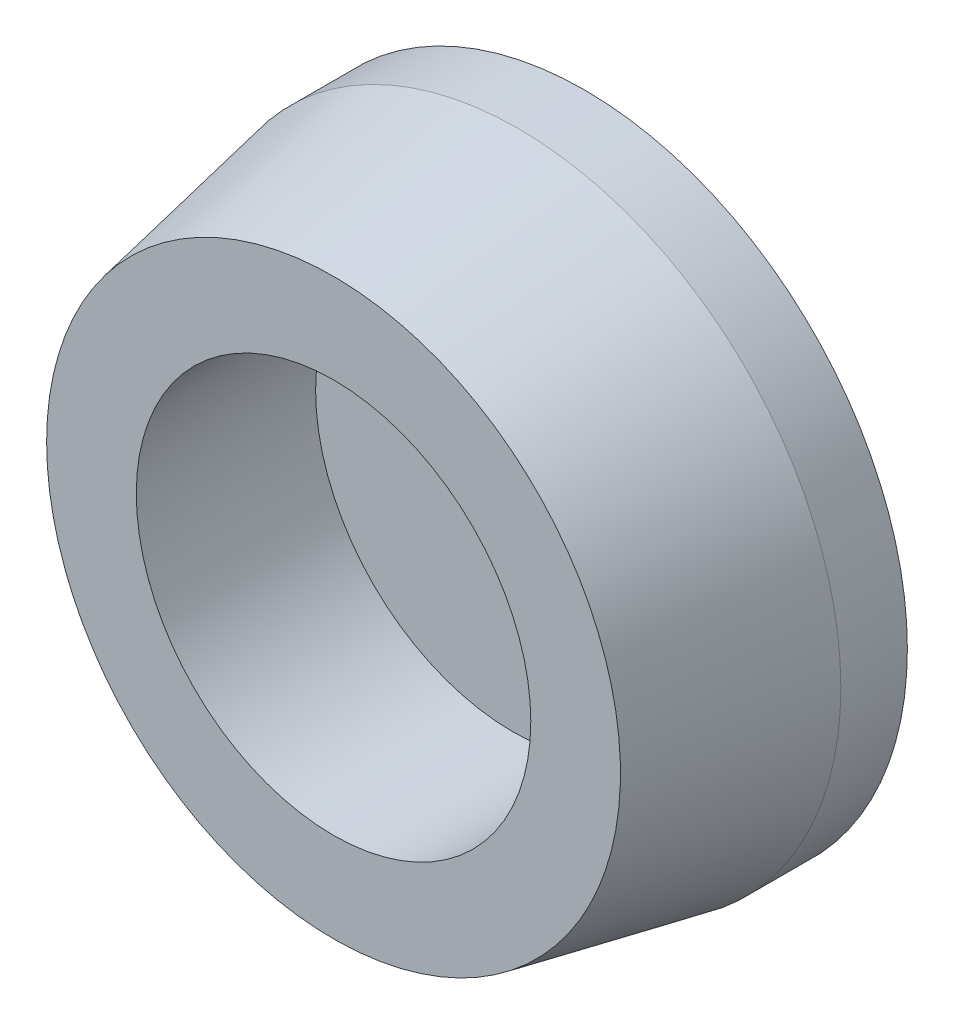
SolidWorks part; units mm, degrees
ref_plane "Front Plane" through (0, 0, 0) normal (0, 0, 1) x (1, 0, 0)
ref_plane "Top Plane" through (0, 0, 0) normal (0, 1, 0) x (1, 0, 0)
ref_plane "Right Plane" through (0, 0, 0) normal (1, 0, 0) x (0, 0, -1)
sketch "Sketch1" plane through (0, 0, 0) normal (0, 0, 1) x (1, 0, 0)
  circle A0 centre (0, 0) radius 9
  dimension "D1" = 18
extrude "Boss-Extrude1" add sketch "Sketch1" along normal blind 7
sketch "Sketch2" plane through (0, 0, 7) normal (0, 0, 1) x (1, 0, 0)
  circle A0 centre (0, 0) radius 5.5
  dimension "D1" = 11
extrude "Cut-Extrude1" cut sketch "Sketch2" against normal blind 5
chamfer "Chamfer1" distance 1 angle 79 1 edges at (9, 0, 7)
